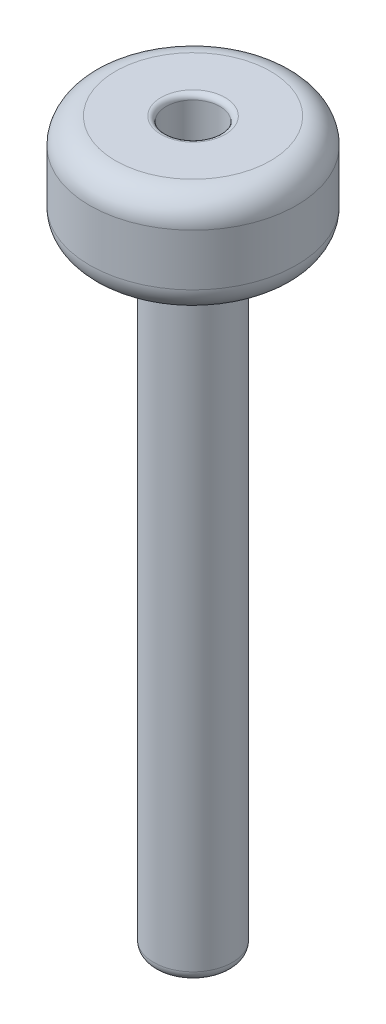
SolidWorks part; units mm, degrees
ref_plane "Front" through (0, 0, 0) normal (0, 0, 1) x (1, 0, 0)
ref_plane "Top" through (0, 0, 0) normal (0, 1, 0) x (1, 0, 0)
ref_plane "Right" through (0, 0, 0) normal (1, 0, 0) x (0, 0, -1)
other "Configuration Table"
sketch "草图1" plane through (0, 0, 0) normal (0, 1, 0) x (1, 0, 0)
  circle A0 centre (0, 0) radius 7.6
  circle A1 centre (0, 0) radius 5.2
extrude "凸台-拉伸1" add sketch "草图1" along normal blind 120
sketch "草图2" plane through (0, 120, 0) normal (0, 1, 0) x (1, 0, 0)
  circle A0 centre (0, 0) radius 20
extrude "凸台-拉伸2" add sketch "草图2" along normal blind 20
sketch "草图3" plane through (0, 140, 0) normal (0, 1, 0) x (1, 0, 0)
  circle A0 centre (0, 0) radius 5.2
extrude "切除-拉伸1" cut sketch "草图3" against normal blind 157
fillet "圆角1" radius 5 2 edges at (0, 120, 20) (0, 140, 20)
fillet "圆角2" radius 2 2 edges at (0, 120, 7.6) (0, 0, 7.6)
fillet "圆角3" radius 1 1 edges at (0, 140, 5.2)
